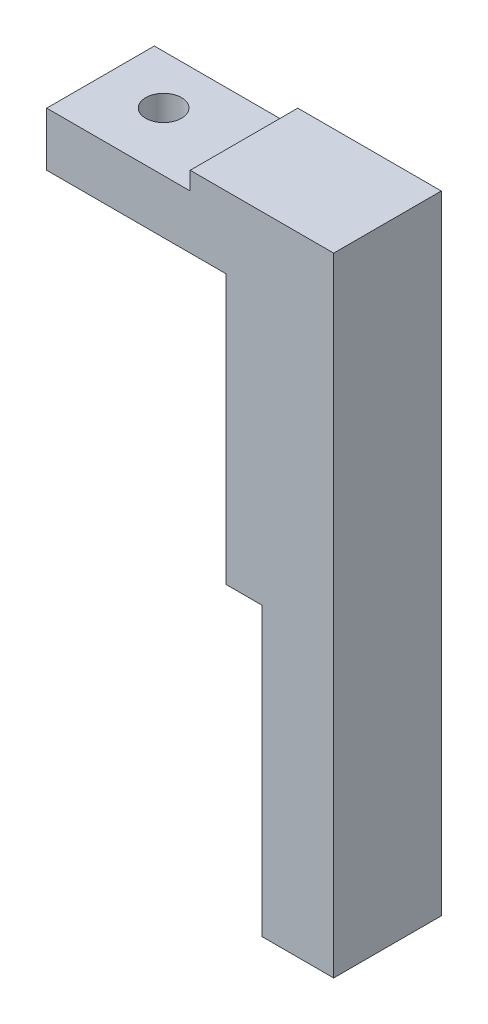
SolidWorks part; units mm, degrees
ref_plane "Front Plane" through (0, 0, 0) normal (0, 0, 1) x (1, 0, 0)
ref_plane "Top Plane" through (0, 0, 0) normal (0, 1, 0) x (1, 0, 0)
ref_plane "Right Plane" through (0, 0, 0) normal (1, 0, 0) x (0, 0, -1)
sketch "Sketch1" plane through (0, 0, 0) normal (0, 1, 0) x (1, 0, 0)
  line L1 (0, 0) -> (15, 0)
  line L2 (0, 0) -> (0, -6)
  line L3 (0, -6) -> (15, -6)
  line L4 (15, 0) -> (15, -6)
  dimension "D1" = 15
  dimension "D2" = 6
extrude "Boss-Extrude1" add sketch "Sketch1" along normal blind 3
sketch "Sketch2" plane through (0, 3, 0) normal (0, 1, 0) x (1, 0, 0)
  line L0 (0, 0) -> (0, -6) construction
  circle A0 centre (3.25, -2.7332) radius 1
  dimension "D2" = 2
  dimension "D1" = 3.25
extrude "Cut-Extrude1" cut sketch "Sketch2" against normal up to next
sketch "Sketch3" plane through (0, 0, 0) normal (0, -1, 0) x (1, 0, 0)
  line L0 (15, 0) -> (0, 0) construction
  line L1 (15, 6) -> (12, 6)
  line L2 (15, 6) -> (15, 0)
  line L3 (15, 0) -> (12, 0)
  line L4 (12, 6) -> (12, 0)
  dimension "D1" = 3
extrude "Boss-Extrude2" add sketch "Sketch3" along normal blind 31
sketch "Sketch4" plane through (15, 0, 0) normal (1, 0, 0) x (0, 0, -1)
  line L1 (-6, 3) -> (0, 3)
  line L2 (-6, 3) -> (-6, -31)
  line L3 (-6, -31) -> (0, -31)
  line L4 (0, 3) -> (0, -31)
extrude "Boss-Extrude3" add sketch "Sketch4" along normal blind 1
sketch "Sketch5" plane through (0, 3, 0) normal (0, 1, 0) x (1, 0, 0)
  line L0 (16, 0) -> (0, 0) construction
  line L1 (8, 0) -> (16, 0)
  line L2 (8, 0) -> (8, -6)
  line L3 (8, -6) -> (16, -6)
  line L4 (16, 0) -> (16, -6)
extrude "Boss-Extrude4" add sketch "Sketch5" along normal blind 1
sketch "Sketch6" plane through (0, 0, 0) normal (0, 0, 1) x (1, 0, 0)
  line L0 (12, -31) -> (12, 0) construction
  line L1 (0, 0) -> (12, 0) construction
  line L3 (10, 0) -> (12, 0)
  line L4 (10, 0) -> (10, -15)
  line L5 (10, -15) -> (12, -15)
  line L6 (12, 0) -> (12, -15)
  point P0 (12, 0)
  point P1 (12, -15)
  point P3 (12, -31)
  point P6 (10, 0)
extrude "Boss-Extrude5" add sketch "Sketch6" along normal blind 6
ref_plane "Plane1" through (16, 4, 0) normal (0, 1, 0) x (1, 0, 0)
ref_plane "Plane2" through (16, 4, 0) normal (0, 0, -1) x (-1, 0, 0)
